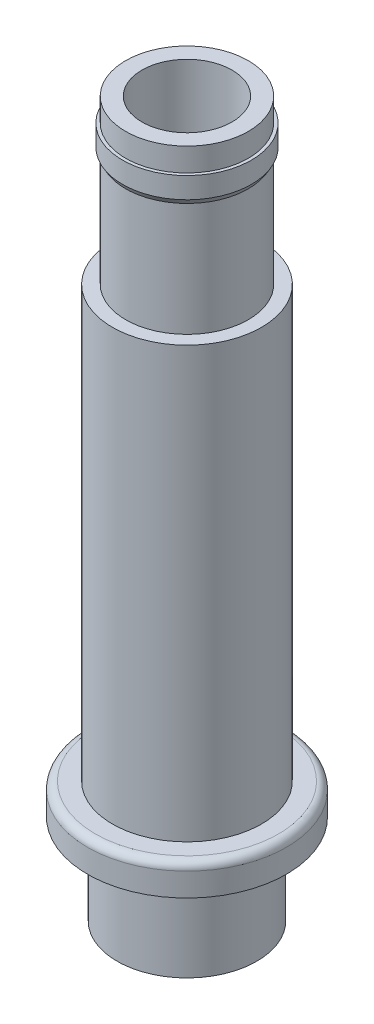
SolidWorks part; units mm, degrees
ref_plane "Front Plane" through (0, 0, 0) normal (0, 0, 1) x (1, 0, 0)
ref_plane "Top Plane" through (0, 0, 0) normal (0, 1, 0) x (1, 0, 0)
ref_plane "Right Plane" through (0, 0, 0) normal (1, 0, 0) x (0, 0, -1)
sketch "Sketch1" plane through (0, 0, 0) normal (1, 0, 0) x (0, 0, -1)
  line L0 (0, 0) -> (0, 46) construction
  line L1 (3.15, 33) -> (3.15, 6.8)
  line L2 (3.15, 6.8) -> (3.5, 6.8)
  line L3 (3.5, 6.8) -> (3.5, 0)
  line L4 (3.5, 0) -> (4.5, 0)
  line L5 (4.5, 0) -> (4.5, 6.8)
  line L6 (4.5, 6.8) -> (5.4, 6.8)
  line L7 (5.4, 6.8) -> (5.4, 5.8)
  line L8 (5.4, 5.8) -> (6.4, 5.8)
  line L9 (6.4, 5.8) -> (6.4, 7.8)
  line L10 (6.4, 7.8) -> (4.8, 7.8)
  line L11 (4.8, 7.8) -> (4.8, 35.5)
  line L12 (4.8, 35.5) -> (3.95, 35.5)
  line L13 (3.95, 35.5) -> (3.95, 42.8)
  line L14 (3.95, 42.8) -> (4.15, 43.1464)
  line L15 (4.15, 43.1464) -> (4.15, 44.5)
  line L16 (4.15, 44.5) -> (3.95, 44.5)
  line L17 (3.95, 44.5) -> (3.95, 46)
  line L18 (3.95, 46) -> (2.9, 46)
  line L19 (2.9, 46) -> (2.9, 37.5)
  line L20 (2.9, 37.5) -> (1.75, 34)
  line L22 (1.75, 34) -> (1.75, 33)
  line L23 (1.75, 33) -> (3.15, 33)
  dimension "D1" = 46
  dimension "D2" = 6.8
  dimension "D3" = 5.8
  dimension "D4" = 7.8
  dimension "D5" = 7.3
  dimension "D6" = 1.5
  dimension "D7" = 10.5
  dimension "D8" = 30
  dimension "D9" = 8.5
  dimension "D10" = 3.5
  dimension "D11" = 6.8
  dimension "D12" = 6.3
  dimension "D13" = 9
  dimension "D14" = 9.6
  dimension "D15" = 12.8
  dimension "D16" = 7
  dimension "D17" = 1
  dimension "D18" = 7.9
  dimension "D19" = 8.3
  dimension "D20" = 5.8
  dimension "D21" = 33
  dimension "D22" = 3.5
revolve "Revolve1" add sketch "Sketch1" angle 360 about L0
fillet "Fillet1" radius 0.5 1 edges at (0, 7.8, -6.4)
sketch "Sketch2" plane through (0, 0, 0) normal (0, 1, 0) x (-1, 0, 0)
  line L0 (0, 0) -> (0, 3.15) construction
  line L2 (-0.35, 3.15) -> (0.35, 3.15)
  line L3 (-0.35, 3.15) -> (-0.35, 2.15)
  line L4 (-0.35, 2.15) -> (0.35, 2.15)
  line L5 (0.35, 3.15) -> (0.35, 2.15)
  point P10 (0, 3.15)
  dimension "D1" = 1
  dimension "D2" = 0.7
extrude "Boss-Extrude1" add sketch "Sketch2" along normal up to next from offset 14
pattern_circular "CirPattern1" count 4 over 360 about axis through (0, 0, 0) along (0, 1, 0) of "Boss-Extrude1"
